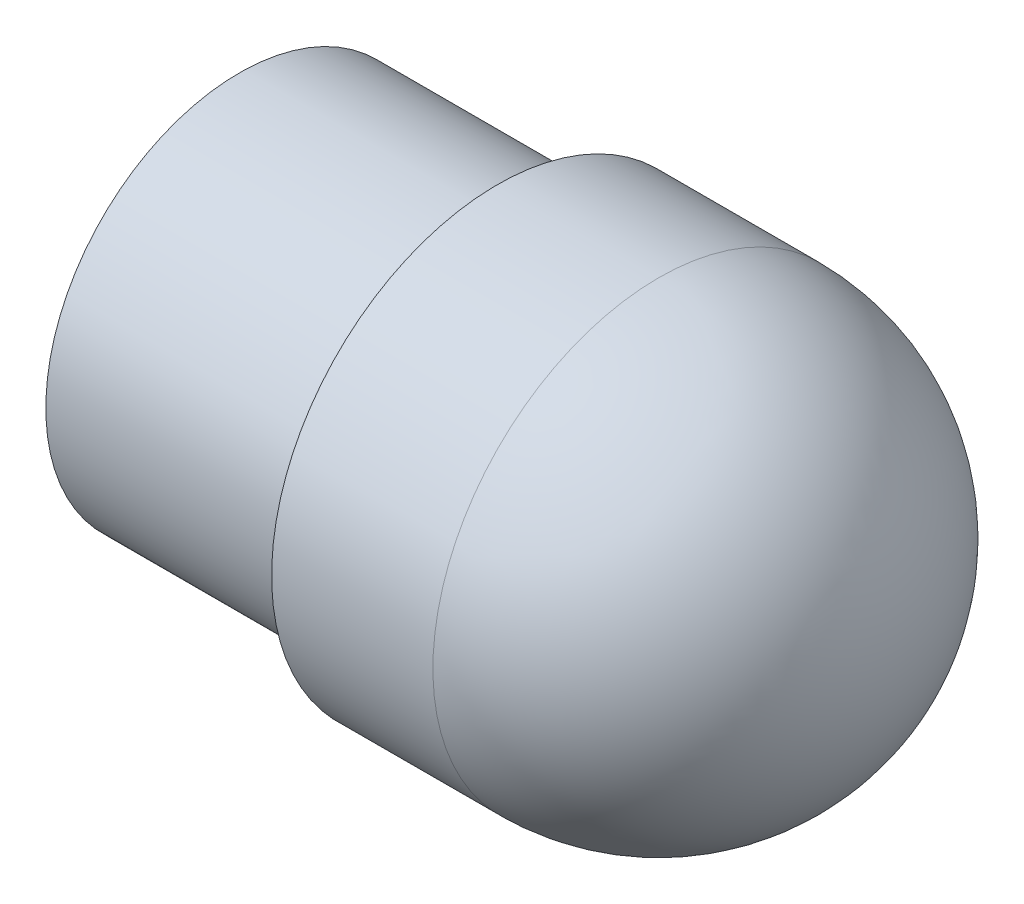
SolidWorks part; units mm, degrees
ref_plane "Alzado" through (0, 0, 0) normal (0, 0, 1) x (1, 0, 0)
ref_plane "Planta" through (0, 0, 0) normal (0, 1, 0) x (1, 0, 0)
ref_plane "Vista lateral" through (0, 0, 0) normal (1, 0, 0) x (0, 0, -1)
sketch "Croquis1" plane through (0, 0, 0) normal (0, 0, 1) x (1, 0, 0)
  line L0 (0, 0) -> (-50, 0)
  line L1 (-50, 0) -> (-50, 15)
  line L2 (-50, 15) -> (-30, 15)
  line L3 (-30, 15) -> (-30, 17.5)
  line L4 (-30, 17.5) -> (-17.5, 17.5)
  arc A0 (-17.5, 17.5) -> (0, 0) centre (-17.5, 0) cw
  point P8 (-13.5065, 16.6883)
  point P9 (0, 0)
  point P10 (-15.3893, 15.3893)
  point P11 (-24.8995, 12.1302)
  dimension "D3" = 17.5
  dimension "D1" = 50
  dimension "D2" = 15
  dimension "D4" = 20
revolve "Revolución1" add sketch "Croquis1" angle 360 about L0
